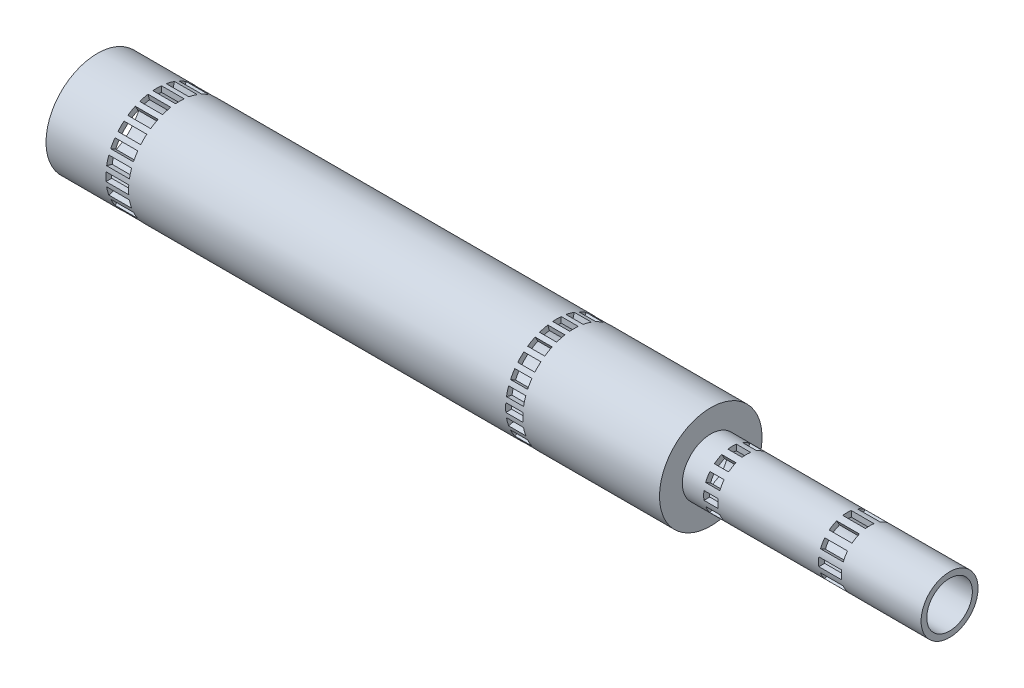
SolidWorks part; units mm, degrees
ref_plane "Front Plane" through (0, 0, 0) normal (0, 0, 1) x (1, 0, 0)
ref_plane "Top Plane" through (0, 0, 0) normal (0, 1, 0) x (1, 0, 0)
ref_plane "Right Plane" through (0, 0, 0) normal (1, 0, 0) x (0, 0, -1)
sketch "Sketch1" plane through (0, 0, 0) normal (0, 0, 1) x (1, 0, 0)
  line L0 (0.2352, 0) -> (215.3473, 0) construction
  line L1 (216.6368, 10) -> (215.3473, 10)
  line L2 (0, 0) -> (299.1651, 0)
  line L5 (299.1651, 10) -> (216.6368, 10)
  line L9 (0, 0) -> (0, 18)
  line L10 (0, 18) -> (215.3473, 18)
  line L14 (215.3473, 18) -> (215.3473, 10.316)
  line L24 (215.3473, 10.316) -> (215.3473, 10)
  line L28 (299.1651, 10) -> (299.1651, 0)
  line L29 (299.1651, 0) -> (215.3473, 0) construction
  dimension "D1" = 10
  dimension "D2" = 18
revolve "Revolve2" add sketch "Sketch1" angle 360 about L2
shell "Shell1" thickness 2
ref_plane "Plane1" through (21, 0, 0) normal (-1, 0, 0) x (0, 0, 1)
sketch "Sketch2" plane through (21, 0, 0) normal (-1, 0, 0) x (0, 0, 1)
  line L0 (0, 0) -> (-21.7788, 0) construction
  line L2 (-18.6962, 1.5) -> (-15.1587, 1.5)
  line L3 (-18.6962, 1.5) -> (-18.6962, -1.5)
  line L4 (-18.6962, -1.5) -> (-15.1587, -1.5)
  line L5 (-15.1587, 1.5) -> (-15.1587, -1.5)
  line L6 (-18.6962, 1.5) -> (-15.1587, -1.5) construction
  line L7 (-18.6962, -1.5) -> (-15.1587, 1.5) construction
  point P3 (-16.9274, 0)
  point P8 (0, 0)
  dimension "D1" = 3
extrude "Cut-Extrude1" cut sketch "Sketch2" against normal blind 8
pattern_circular "CirPattern1" count 24 over 360 about axis through (0, 0, 0) along (1, 0, 0) of "Cut-Extrude1"
ref_plane "Plane2" through (167.3473, 0, 0) normal (1, 0, 0) x (0, 0, -1)
sketch "Sketch4" plane through (167.3473, 0, 0) normal (1, 0, 0) x (0, 0, -1)
  line L0 (0, 0) -> (-24.5819, 0) construction
  line L1 (-20.4382, 1.5) -> (-15.5618, 1.5)
  line L2 (-20.4382, 1.5) -> (-20.4382, -1.5)
  line L3 (-20.4382, -1.5) -> (-15.5618, -1.5)
  line L4 (-15.5618, 1.5) -> (-15.5618, -1.5)
  line L5 (-20.4382, 1.5) -> (-15.5618, -1.5) construction
  line L6 (-20.4382, -1.5) -> (-15.5618, 1.5) construction
  circle A0 centre (0, 0) radius 18 construction
  point P0 (-18, 0)
  dimension "D1" = 3
extrude "Cut-Extrude2" cut sketch "Sketch4" against normal blind 6
pattern_circular "CirPattern2" count 24 over 360 about axis through (0, 0, 0) along (1, 0, 0) of "Cut-Extrude2"
ref_plane "Plane4" through (271.1651, 0, 0) normal (1, 0, 0) x (0, 0, -1)
sketch "Sketch6" plane through (271.1651, 0, 0) normal (1, 0, 0) x (0, 0, -1)
  line L0 (11.2057, 0) -> (-11.2057, 0) construction
  line L2 (-14.0433, 1.5) -> (-6.0433, 1.5)
  line L3 (-14.0433, 1.5) -> (-14.0433, -1.5)
  line L4 (-14.0433, -1.5) -> (-6.0433, -1.5)
  line L5 (-6.0433, 1.5) -> (-6.0433, -1.5)
  line L6 (-14.0433, 1.5) -> (-6.0433, -1.5) construction
  line L7 (-14.0433, -1.5) -> (-6.0433, 1.5) construction
  point P0 (-10.0433, 0)
  point P6 (0, 0)
  dimension "D1" = 3
  dimension "D2" = 8
extrude "Cut-Extrude3" cut sketch "Sketch6" against normal blind 8 contours L3 L2 L5 L4
pattern_circular "CirPattern5" count 12 over 360 about axis through (0, 0, 0) along (1, 0, 0) of "Cut-Extrude3"
ref_plane "Plane5" through (227.8473, 0, 0) normal (1, 0, 0) x (0, 0, -1)
sketch "Sketch7" plane through (227.8473, 0, 0) normal (1, 0, 0) x (0, 0, -1)
  line L0 (0, 0) -> (-10.0974, 0) construction
  line L6 (-10.5488, 1.5) -> (-5.5488, 1.5)
  line L7 (-10.5488, 1.5) -> (-10.5488, -1.5)
  line L12 (-10.5488, -1.5) -> (-5.5488, -1.5)
  line L13 (-5.5488, 1.5) -> (-5.5488, -1.5)
  line L14 (-10.5488, 1.5) -> (-5.5488, -1.5) construction
  line L15 (-10.5488, -1.5) -> (-5.5488, 1.5) construction
  point P3 (-8.0488, 0)
extrude "Cut-Extrude28" cut sketch "Sketch7" against normal blind 5 contours L7 L6 L13 L12
pattern_circular "CirPattern7" count 12 over 360 about axis through (0, 0, 0) along (1, 0, 0) of "Cut-Extrude28"
